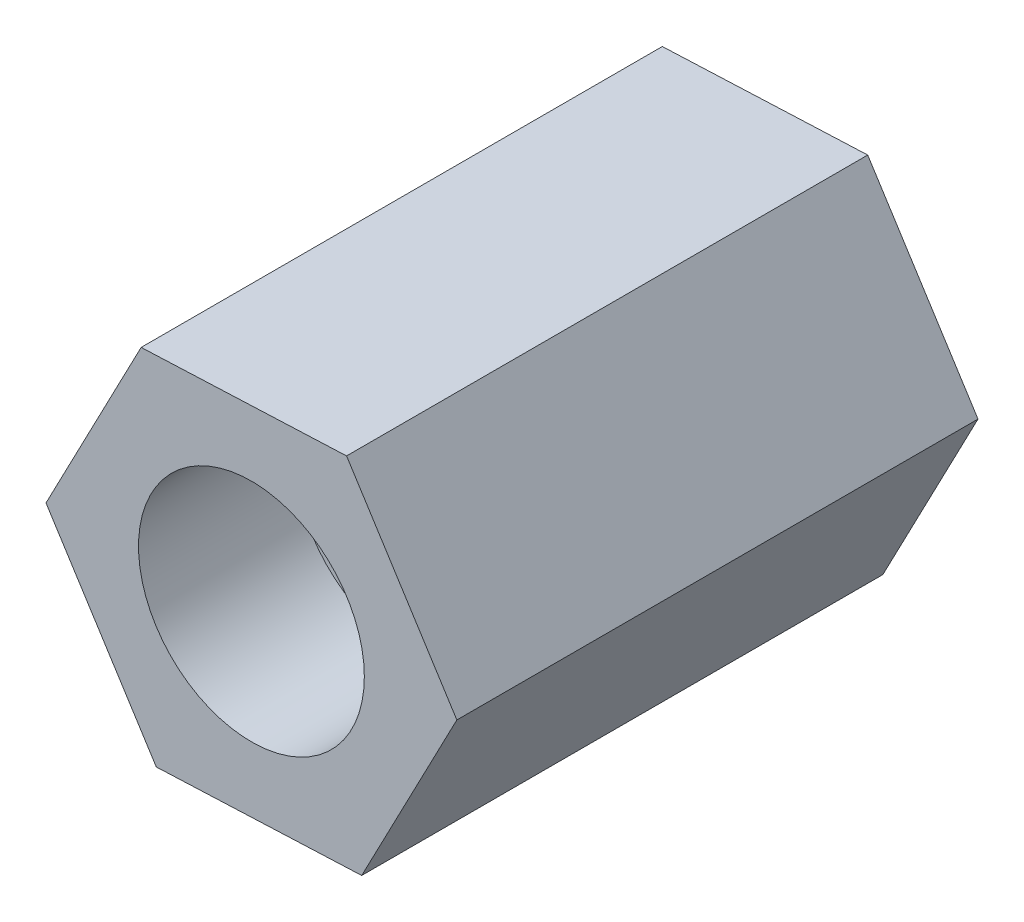
SolidWorks part; units mm, degrees
ref_plane "前视基准面" through (0, 0, 0) normal (0, 0, 1) x (1, 0, 0)
ref_plane "上视基准面" through (0, 0, 0) normal (0, 1, 0) x (1, 0, 0)
ref_plane "右视基准面" through (0, 0, 0) normal (1, 0, 0) x (0, 0, -1)
sketch "草图1" plane through (0, 0, 0) normal (0, 0, 1) x (1, 0, 0)
  line L1 (-12.6957, 19.9788) -> (-23.65, -1.0054)
  line L2 (-23.65, -1.0054) -> (-10.9543, -20.9842)
  line L3 (-10.9543, -20.9842) -> (12.6957, -19.9788)
  line L4 (12.6957, -19.9788) -> (23.65, 1.0054)
  line L5 (23.65, 1.0054) -> (10.9543, 20.9842)
  line L6 (10.9543, 20.9842) -> (-12.6957, 19.9788)
  circle A0 centre (0, 0) radius 20.5 construction
  dimension "D1" = 41
  dimension "D2" = 47.3
extrude "凸台-拉伸1" add sketch "草图1" along normal blind 60
sketch "草图2" plane through (0, 0, 60) normal (0, 0, 1) x (1, 0, 0)
  circle A0 centre (0, 0) radius 13
  dimension "D1" = 26
extrude "切除-拉伸1" cut sketch "草图2" against normal blind 18
sketch "草图3" plane through (0, 0, 42) normal (0, 0, 1) x (1, 0, 0)
  circle A0 centre (0, 0) radius 11.1
  dimension "D1" = 22.2
extrude "切除-拉伸2" cut sketch "草图3" against normal through all
